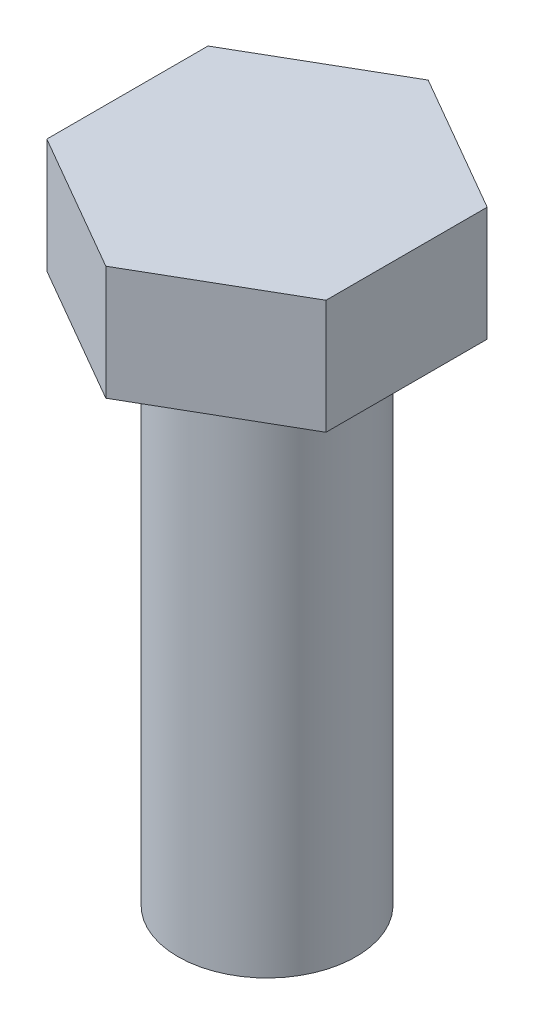
SolidWorks part; units mm, degrees
ref_plane "Front Plane" through (0, 0, 0) normal (0, 0, 1) x (1, 0, 0)
ref_plane "Top Plane" through (0, 0, 0) normal (0, 1, 0) x (1, 0, 0)
ref_plane "Right Plane" through (0, 0, 0) normal (1, 0, 0) x (0, 0, -1)
sketch "Sketch1" plane through (0, 0, 0) normal (0, 1, 0) x (1, 0, 0)
  line L1 (0, 10.8542) -> (-9.4, 5.4271)
  line L2 (-9.4, 5.4271) -> (-9.4, -5.4271)
  line L3 (-9.4, -5.4271) -> (0, -10.8542)
  line L4 (0, -10.8542) -> (9.4, -5.4271)
  line L5 (9.4, -5.4271) -> (9.4, 5.4271)
  line L6 (9.4, 5.4271) -> (0, 10.8542)
  circle A0 centre (0, 0) radius 9.4 construction
  dimension "D1" = 18.8
  dimension "D2" = 21.7084
extrude "Boss-Extrude1" add sketch "Sketch1" along normal blind 7.7
sketch "Sketch2" plane through (0, 0, 0) normal (0, -1, 0) x (1, 0, 0)
  circle A0 centre (0, 0) radius 6
  dimension "D1" = 12
extrude "Boss-Extrude2" add sketch "Sketch2" along normal blind 35
thread "Thread1" pitch 1.5 start angle 0, offset 0, length 0, pitch 1.5, diameter 12
ref_plane "Plane1" through (-6, 0, 0) normal (0, 0, 1) x (-1, 0, 0)
sketch "Thread Profile1" plane through (-6, 0, 0) normal (0, 0, 1) x (-1, 0, 0)
  line L0 (0, 0) -> (0, 1.5) construction
  line L11 (0, 0) -> (0, 1.3125)
  line L12 (0, 1.3125) -> (-0.8119, 0.8437)
  line L13 (-0.8119, 0.8437) -> (-0.8119, 0.4687)
  line L15 (-0.8119, 0.4687) -> (0, 0)
  line L17 (-0.8119, 0.6562) -> (0, 0.6562) construction
  point P2 (0, 0)
  dimension "Pitch" = 1.5
  dimension "Profile_Angle" = 60
  dimension "Profile_Land" = 0.375
  dimension "Profile_Height" = 0.8119
